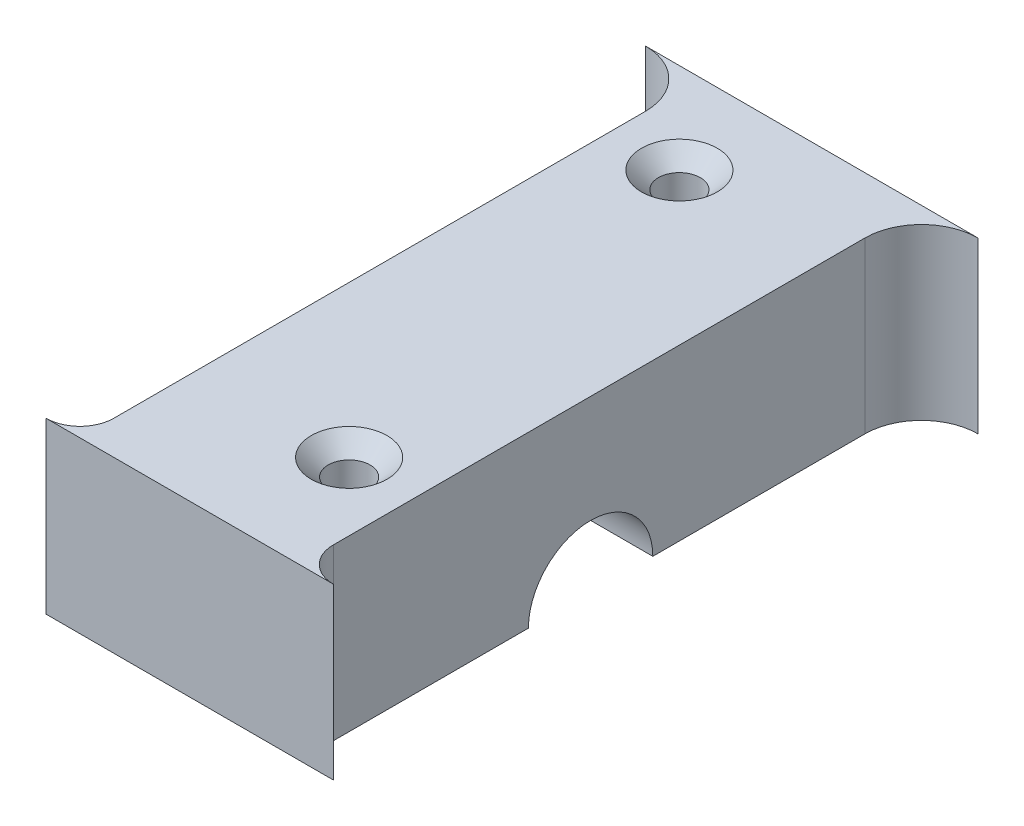
SolidWorks part; units mm, degrees
ref_plane "Plano frontal" through (0, 0, 0) normal (0, 0, 1) x (1, 0, 0)
ref_plane "Plano superior" through (0, 0, 0) normal (0, 1, 0) x (1, 0, 0)
ref_plane "Plano direito" through (0, 0, 0) normal (1, 0, 0) x (0, 0, -1)
sketch "Esboço1" plane through (0, 0, 0) normal (0, 1, 0) x (1, 0, 0)
  line L0 (3, 50) -> (3, 3)
  line L1 (0, 0) -> (25.4, 0)
  line L5 (12.7, 55) -> (12.7, 0) construction
  line L7 (27.4, 55) -> (-2, 55)
  line L8 (22.4, 50) -> (22.4, 3)
  arc A4 (0, 0) -> (3, 3) centre (0, 3) ccw
  arc A7 (-2, 55) -> (3, 50) centre (-2, 50) cw
  arc A8 (27.4, 55) -> (22.4, 50) centre (27.4, 50) ccw
  arc A9 (25.4, 0) -> (22.4, 3) centre (25.4, 3) cw
  dimension "D2" = 5
  dimension "D3" = 3
  dimension "D1" = 47
  dimension "D4" = 3
  dimension "D5" = 3
  dimension "D6" = 5
  dimension "D7" = 5
  dimension "D8" = 29.4
extrude "Corpo" add sketch "Esboço1" along normal blind 15
ref_plane "Plano de Referência" through (12.7, 0, 0) normal (1, 0, 0) x (0, 0, -1)
sketch "Esboço3" plane through (12.7, 0, 0) normal (1, 0, 0) x (0, 0, -1)
  line L1 (55, 15) -> (55, 0) construction
  line L3 (3, 15) -> (50, 15) construction
  circle A0 centre (25.75, 0) radius 5.5
  point P4 (26.5, 0)
  dimension "D1" = 11
  dimension "D3" = 15
  dimension "D2" = 29.25
extrude "Encaixe Flange - Ø11 Passante" cut sketch "Esboço3" against normal through all and the other way through all
sketch "Esboço4" plane through (12.7, 0, 0) normal (1, 0, 0) x (0, 0, -1)
  circle A0 centre (25.75, 0) radius 11.5
  dimension "D1" = 23
extrude "Encaixe Flange - Ø23x4" cut sketch "Esboço4" against normal blind 2 and the other way blind 2
sketch "Esboço6" plane through (0, 0, 0) normal (0, -1, 0) x (1, 0, 0)
  line L0 (0, 0) -> (25.4, 0) construction
  line L1 (22.4, -3) -> (22.4, -20.25) construction
  line L2 (27.4, -55) -> (-2, -55) construction
  line L3 (3, -50) -> (3, -31.25) construction
  circle A0 centre (16.4, -10.4) radius 1.85
  circle A1 centre (9, -47) radius 1.85
  dimension "D1" = 3.7
  dimension "D2" = 10.4
  dimension "D3" = 6
  dimension "D4" = 8
  dimension "D5" = 6
extrude "Furos de Fixação" cut sketch "Esboço6" against normal through all
chamfer "Escareado 1.5x45°" distance 1.5 angle 45 2 edges at (9, 15, -48.85) (16.4, 15, -12.25)
